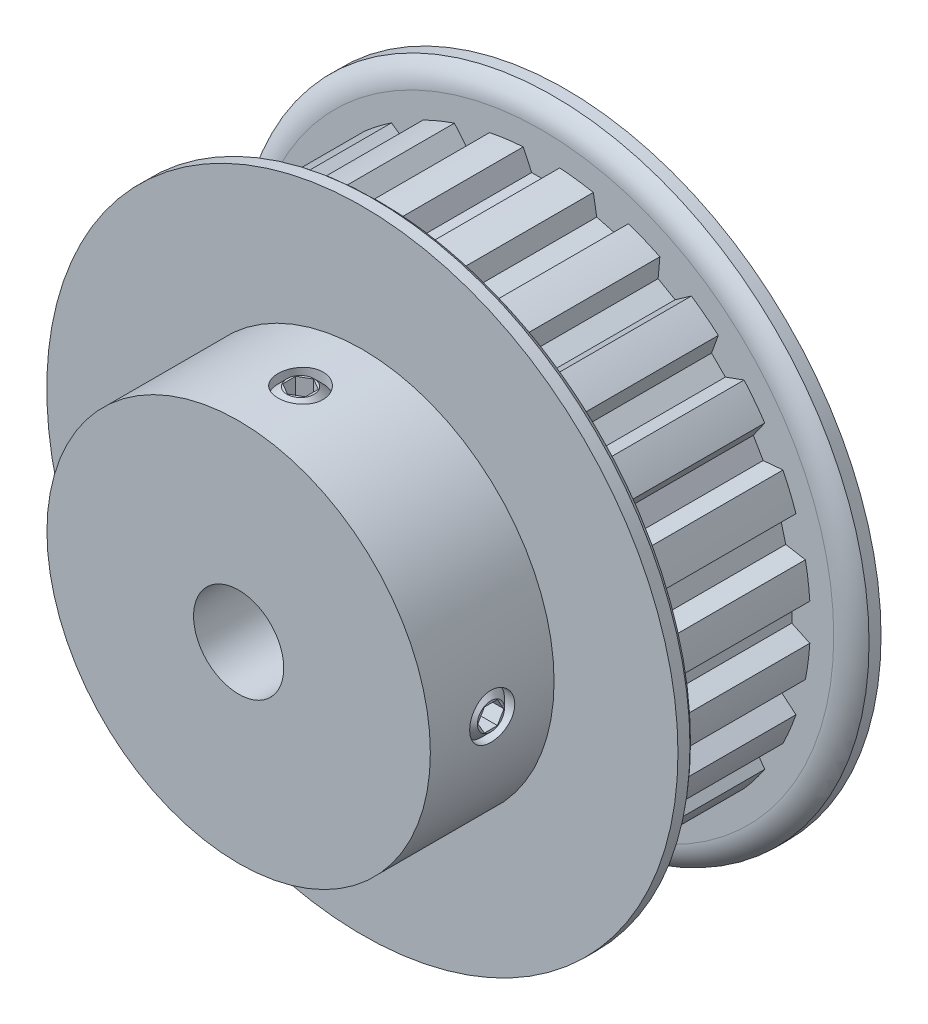
SolidWorks part; units mm, degrees
ref_plane "Front Plane" through (0, 0, 0) normal (0, 0, 1) x (1, 0, 0)
ref_plane "Top Plane" through (0, 0, 0) normal (0, 1, 0) x (1, 0, 0)
ref_plane "Right Plane" through (0, 0, 0) normal (1, 0, 0) x (0, 0, -1)
sketch "Sketch1" plane through (0, 0, 0) normal (0, 0, 1) x (1, 0, 0)
  line L0 (-1.2827, 18.8976) -> (-0.6905, 17.6276)
  line L1 (-0.6905, 17.6276) -> (0.6905, 17.6276)
  line L2 (0.6905, 17.6276) -> (1.2827, 18.8976)
  line L3 (-1.2827, 18.8976) -> (1.2827, 18.8976)
  line L4 (0, 0) -> (0, 17.6276) construction
  line L5 (0, 17.6276) -> (0, 19.9136) construction
  circle A0 centre (0, 0) radius 19.4056 construction
  circle A1 centre (0, 0) radius 22.225 construction
  circle A2 centre (0, 0) radius 18.9411 construction
  point P6 (0, 18.8976)
  point P11 (0, 19.4056)
  point P13 (0, 22.225)
  point P14 (0, 18.9411)
  dimension "D1" = 1.016
  dimension "PD" = 38.8112
  dimension "D2" = 0.508
  dimension "OD" = 44.45
  dimension "b" = 50
  dimension "bt" = 2.5654
  dimension "ht" = 1.27
  dimension "hs" = 2.286
sketch "Sketch2" plane through (0, 0, 0) normal (1, 0, 0) x (0, 0, -1)
  line L0 (-11.5062, 3.175) -> (11.5062, 3.175)
  line L1 (-11.5062, 3.175) -> (-11.5062, 13.5001)
  line L2 (-11.5062, 13.5001) -> (-2.794, 13.5001)
  line L3 (-2.794, 13.5001) -> (-2.794, 22.225)
  line L4 (-2.794, 22.225) -> (-1.1049, 22.225) construction
  line L5 (-1.1049, 22.225) -> (-1.1049, 18.9411) construction
  line L6 (-1.1049, 18.9411) -> (9.8171, 18.9411)
  line L7 (9.8171, 18.9411) -> (9.8171, 22.225) construction
  line L8 (9.8171, 22.225) -> (11.5062, 22.225) construction
  line L9 (11.5062, 22.225) -> (11.5062, 3.175)
  line L10 (-11.5062, 0) -> (11.5062, 0) construction
  line L13 (-2.794, 22.225) -> (-1.9495, 22.225)
  line L14 (-1.1049, 20.583) -> (-1.1049, 18.9411)
  line L15 (9.8171, 18.9411) -> (9.8171, 20.583)
  line L16 (10.6616, 22.225) -> (11.5062, 22.225)
  arc A0 (-1.1049, 20.583) -> (-1.9495, 22.225) centre (-3.1233, 20.583) ccw
  arc A1 (9.8171, 20.583) -> (10.6616, 22.225) centre (11.8355, 20.583) cw
  point P12 (-1.1049, 20.583)
  point P14 (-1.9495, 22.225)
  point P20 (9.8171, 20.583)
  point P21 (10.6616, 22.225)
  point P25 (9.8171, 0)
  point P26 (-1.1049, 0)
  dimension "OA" = 23.0124
  dimension "Bore" = 6.35
  dimension "Hub Dia" = 27.0002
  dimension "Outside Width" = 14.3002
  dimension "Inside Width" = 10.922
revolve "Revolve1" add sketch "Sketch2" angle 360 about L10
sketch "Sketch3" plane through (0, 0, 0) normal (0, 0, 1) x (1, 0, 0)
  line L0 (-0.6905, 17.6276) -> (0.6905, 17.6276) construction
  line L1 (0.6905, 17.6276) -> (1.2827, 18.8976) construction
  line L2 (-1.2827, 18.8976) -> (-0.6905, 17.6276) construction
  line L3 (-0.6905, 17.6276) -> (0.6905, 17.6276)
  line L4 (0.6905, 17.6276) -> (1.2827, 18.8976)
  line L5 (-1.2827, 18.8976) -> (-0.6905, 17.6276)
  circle A0 centre (0, 0) radius 18.9411 construction
  arc A1 (1.2827, 18.8976) -> (-1.2827, 18.8976) centre (0, 0) ccw
extrude "Cut-Extrude1" cut sketch "Sketch3" against normal up to vertex (9.8171 mm away) from vertex at 1.1049 starting at point (0, 18.9411, 1.1049)
pattern_circular "CirPattern1" count 24 over 360 about axis through (0, 0, 0) along (0, 0, 1) of "Cut-Extrude1"
sketch "Sketch4" plane through (0, 0, 0) normal (0, 1, 0) x (1, 0, 0)
  line L0 (0, -2.794) -> (0, -11.5062) construction
  line L1 (-13.5001, -2.794) -> (13.5001, -2.794) construction
  line L2 (-13.5001, -11.5062) -> (13.5001, -11.5062) construction
  circle A0 centre (0, -7.1501) radius 1.5875
  dimension "D1" = 3.175
extrude "Cut-Extrude2" cut sketch "Sketch4" along normal through all
ref_plane "Plane1" through (0, 0, 7.1501) normal (0, 0, 1) x (1, 0, 0)
sketch "Sketch5" plane through (0, 0, 7.1501) normal (0, 0, 1) x (1, 0, 0)
  line L0 (0, 0) -> (0, 13.5001) construction
  line L1 (-1.5875, 13.4064) -> (-1.5875, 2.7496) construction
  line L2 (-1.5875, 13.4064) -> (-1.5875, 2.7496) construction
  line L3 (0, 13.4064) -> (0, 3.175)
  line L4 (0, 3.175) -> (-0.9525, 3.175)
  line L5 (-1.5875, 12.7714) -> (-1.5875, 3.81)
  line L6 (-0.9525, 13.4064) -> (0, 13.4064)
  line L7 (-1.5875, 12.7714) -> (-0.9525, 13.4064)
  line L8 (-1.5875, 3.81) -> (-0.9525, 3.175)
  circle A0 centre (0, 0) radius 13.5001 construction
  circle A3 centre (0, 0) radius 3.175 construction
  point P13 (-1.5875, 3.175)
  point P15 (-1.5875, 13.4064)
  dimension "D7" = 0.635
  dimension "D8" = 0.635
revolve "Revolve2" add sketch "Sketch5" angle 360 about L0
sketch "Sketch6" plane through (0, 13.4064, 0) normal (0, -1, 0) x (-1, 0, 0)
  line L1 (0, -6.2336) -> (-0.7938, -6.6918)
  line L2 (-0.7938, -6.6918) -> (-0.7937, -7.6084)
  line L3 (-0.7937, -7.6084) -> (0, -8.0666)
  line L4 (0, -8.0666) -> (0.7938, -7.6084)
  line L5 (0.7938, -7.6084) -> (0.7938, -6.6918)
  line L6 (0.7938, -6.6918) -> (0, -6.2336)
  circle A0 centre (0, -7.1501) radius 0.7938 construction
  dimension "D1" = 1.5875
extrude "Cut-Extrude3" cut sketch "Sketch6" along normal blind 1.1906
pattern_circular "CirPattern2" count 2 every 90 about axis through (0, 0, 0) along (0, 0, 1) of "Cut-Extrude2", "Revolve2", "Cut-Extrude3"
equation "\"D2@Sketch1\" = \"D1@Sketch1\"/2"
equation "\"D1@Sketch4\" = \"Bore@Sketch2\"/2"
equation "\"D1@Sketch6\" = \"D1@Sketch4\"/2"
equation "\"D1@Cut-Extrude3\" = \"D1@Sketch6\"*.75"
